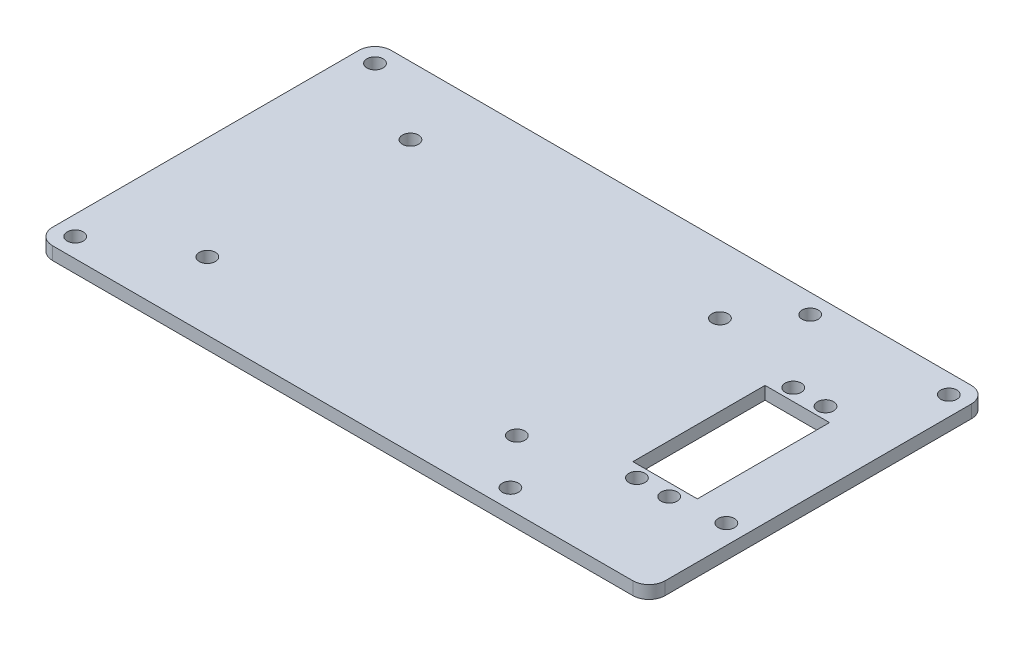
SolidWorks part; units mm, degrees
ref_plane "前视基准面" through (0, 0, 0) normal (0, 0, 1) x (1, 0, 0)
ref_plane "上视基准面" through (0, 0, 0) normal (0, 1, 0) x (1, 0, 0)
ref_plane "右视基准面" through (0, 0, 0) normal (1, 0, 0) x (0, 0, -1)
sketch "草图1" plane through (0, 0, 0) normal (0, 1, 0) x (1, 0, 0)
  line L0 (-89, 46.5) -> (89, 46.5) construction
  line L1 (-95, -52.5) -> (95, -52.5)
  line L2 (-95, -52.5) -> (-95, 52.5)
  line L3 (-95, 52.5) -> (95, 52.5)
  line L4 (95, -52.5) -> (95, 52.5)
  line L5 (-95, -52.5) -> (95, 52.5) construction
  line L6 (-95, 52.5) -> (95, -52.5) construction
  line L7 (89, -46.5) -> (89, 46.5) construction
  line L8 (-89, -46.5) -> (89, -46.5) construction
  line L9 (-89, -46.5) -> (-89, 46.5) construction
  line L10 (-89, 0) -> (89, 0) construction
  line L12 (-63, -31.5) -> (33, -31.5) construction
  line L13 (-63, -31.5) -> (-63, 31.5) construction
  line L14 (-63, 31.5) -> (33, 31.5) construction
  line L15 (33, -31.5) -> (33, 31.5) construction
  line L16 (-63, -31.5) -> (33, 31.5) construction
  line L17 (-63, 31.5) -> (33, -31.5) construction
  line L18 (58, 20.5) -> (78, 20.5)
  line L19 (58, 20.5) -> (58, -20.5)
  line L20 (58, -20.5) -> (78, -20.5)
  line L21 (78, 20.5) -> (78, -20.5)
  line L22 (58, 20.5) -> (78, -20.5) construction
  line L23 (58, -20.5) -> (78, 20.5) construction
  line L24 (63, -24.25) -> (73, -24.25) construction
  line L25 (63, -24.25) -> (63, 24.25) construction
  line L26 (63, 24.25) -> (73, 24.25) construction
  line L27 (73, -24.25) -> (73, 24.25) construction
  line L28 (63, -24.25) -> (73, 24.25) construction
  line L29 (63, 24.25) -> (73, -24.25) construction
  circle A0 centre (-89, 46.5) radius 2.5
  circle A1 centre (89, 46.5) radius 2.5
  circle A2 centre (89, -46.5) radius 2.5 construction
  circle A3 centre (-89, -46.5) radius 2.5
  circle A4 centre (-63, 31.5) radius 2.5
  circle A5 centre (33, 31.5) radius 2.5
  circle A6 centre (-63, -31.5) radius 2.5
  circle A7 centre (33, -31.5) radius 2.5
  circle A8 centre (63, 24.25) radius 2.5
  circle A9 centre (73, 24.25) radius 2.5
  circle A10 centre (63, -24.25) radius 2.5
  circle A11 centre (73, -24.25) radius 2.5
  circle A12 centre (-74, 46.5) radius 2.5 construction
  circle A13 centre (-74, -46.5) radius 2.5 construction
  circle A14 centre (46, -46.5) radius 2.5
  circle A15 centre (46, 46.5) radius 2.5
  circle A16 centre (89, -22.5) radius 2.5
  point P0 (0, 0)
  point P16 (-15, 0)
  point P25 (68, 0)
  point P30 (68, 0)
  dimension "D4" = 5
  dimension "D7" = 5
  dimension "D12" = 5
  dimension "D16" = 2
  dimension "D18" = 135
  dimension "D19" = 135
  dimension "D20" = 69
  dimension "D1" = 190
  dimension "D2" = 105
  dimension "D5" = 96
  dimension "D6" = 63
  dimension "D8" = 20
  dimension "D9" = 41
  dimension "D10" = 25
  dimension "D11" = 17
  dimension "D13" = 10
  dimension "D14" = 48.5
  dimension "D3" = 6
  dimension "D15" = 2
  dimension "D17" = 2
extrude "凸台-拉伸1" add sketch "草图1" along normal blind 4
fillet "圆角1" radius 5 4 edges at (-95, 2, -52.5) (-95, 2, 52.5) (95, 2, 52.5) (95, 2, -52.5)
